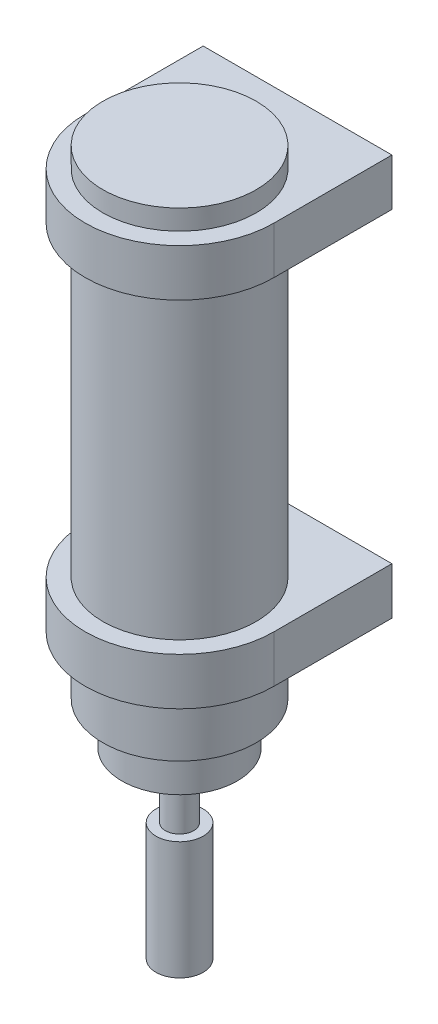
SolidWorks part; units mm, degrees
material "6061-T6/T651 ALLOY"
ref_plane "Front Plane" through (0, 0, 0) normal (0, 0, 1) x (1, 0, 0)
ref_plane "Top Plane" through (0, 0, 0) normal (0, 1, 0) x (1, 0, 0)
ref_plane "Right Plane" through (0, 0, 0) normal (1, 0, 0) x (0, 0, -1)
sketch "Sketch1" plane through (0, 0, 0) normal (0, 0, 1) x (1, 0, 0)
  line L0 (0, 0) -> (0, 248.5) construction
  line L1 (0, 248.5) -> (-32.5, 248.5)
  line L2 (-32.5, 248.5) -> (-32.5, 45.5)
  line L3 (-32.5, 45.5) -> (-24.5, 45.5)
  line L4 (-24.5, 45.5) -> (-24.5, 27.5)
  line L5 (-24.5, 27.5) -> (-6, 27.5)
  line L6 (-6, 27.5) -> (-6, 0)
  line L7 (-6, 0) -> (0, 0)
  line L8 (0, 0) -> (0, 248.5)
  point P3 (-15.25, 27.5)
  dimension "D1" = 32.5
  dimension "D2" = 27.5
  dimension "D3" = 203
  dimension "D4" = 18
  dimension "D5" = 24.5
  dimension "D6" = 6
revolve "Revolve1" add sketch "Sketch1" angle 360 about L0
sketch "Sketch2" plane through (0, 0, 0) normal (0, 1, 0) x (1, 0, 0)
  line L0 (-40, 0) -> (-40, 50)
  line L1 (-40, 50) -> (40, 50)
  line L2 (40, 50) -> (40, 0)
  arc A0 (-40, 0) -> (40, 0) centre (0, 0) ccw
  circle A1 centre (0, 0) radius 32.5 construction
  circle A2 centre (0, 0) radius 32.5
  dimension "D1" = 40
  dimension "D2" = 50
extrude "Boss-Extrude1" add sketch "Sketch2" along normal blind 20 from offset 70
pattern_linear "LPattern1" count 2 spacing 150 along (0, 1, 0) of "Boss-Extrude1"
sketch "Sketch3" plane through (0, 0, 0) normal (0, -1, 0) x (1, 0, 0)
  line L1 (-15.2748, 12.7292) -> (15.4124, 12.7292)
  line L2 (-15.2748, 12.7292) -> (-15.2748, 7.5)
  line L3 (-15.2748, 7.5) -> (15.4124, 7.5)
  line L4 (15.4124, 12.7292) -> (15.4124, 7.5)
  line L5 (-17.3389, -13.142) -> (18.9903, -13.142)
  line L6 (-17.3389, -13.142) -> (-17.3389, -7.5)
  line L7 (-17.3389, -7.5) -> (18.9903, -7.5)
  line L8 (18.9903, -13.142) -> (18.9903, -7.5)
  dimension "D1" = 15
  dimension "D2" = 7.5
extrude "Cut-Extrude1" [suppressed] cut sketch "Sketch3" against normal blind 10
sketch "Sketch4" plane through (0, 0, 0) normal (0, -1, 0) x (1, 0, 0)
  circle A0 centre (0, 0) radius 10
  dimension "D1" = 20
extrude "Boss-Extrude2" add sketch "Sketch4" along normal blind 50
